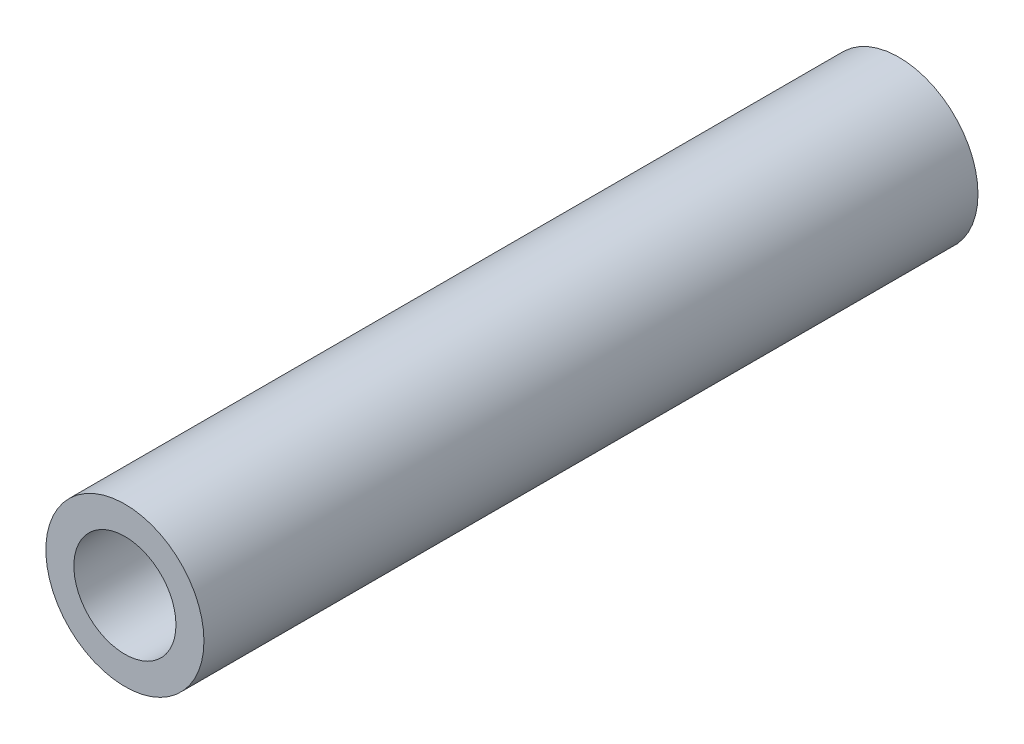
SolidWorks part; units mm, degrees
ref_plane "Front Plane" through (0, 0, 0) normal (0, 0, 1) x (1, 0, 0)
ref_plane "Top Plane" through (0, 0, 0) normal (0, 1, 0) x (1, 0, 0)
ref_plane "Right Plane" through (0, 0, 0) normal (1, 0, 0) x (0, 0, -1)
sketch "Sketch1" plane through (0, 0, 0) normal (0, 0, 1) x (1, 0, 0)
  circle A0 centre (0, 0) radius 2.4
  circle A1 centre (0, 0) radius 1.55
extrude "Boss-Extrude1" add sketch "Sketch1" along normal blind 23.5
